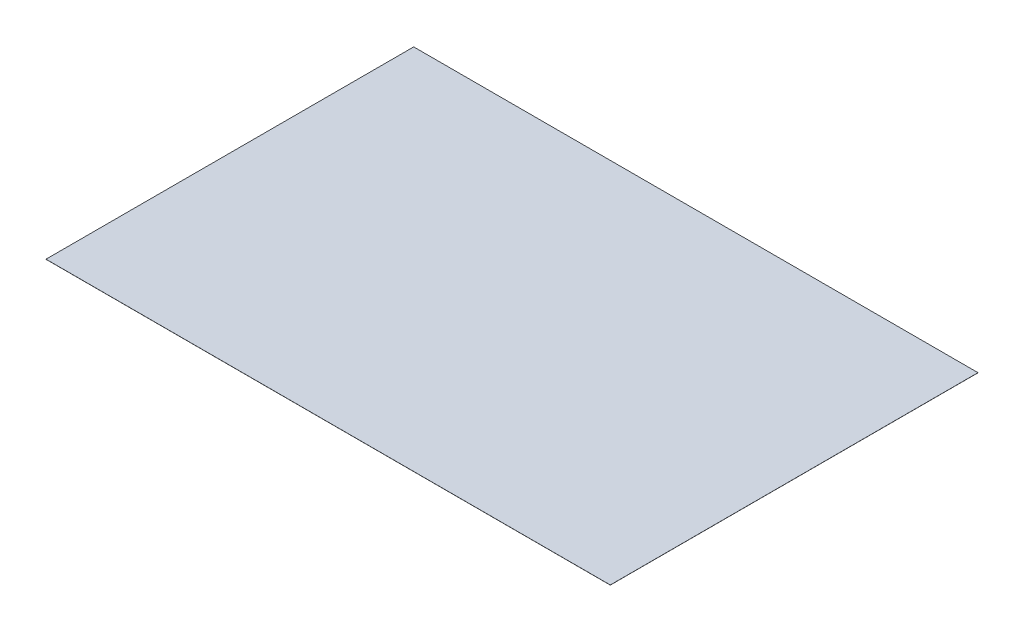
SolidWorks part; units mm, degrees
ref_plane "Front Plane" through (0, 0, 0) normal (0, 0, 1) x (1, 0, 0)
ref_plane "Top Plane" through (0, 0, 0) normal (0, 1, 0) x (1, 0, 0)
ref_plane "Right Plane" through (0, 0, 0) normal (1, 0, 0) x (0, 0, -1)
sketch "Sketch2" plane through (0, 0, 0) normal (0, 1, 0) x (1, 0, 0)
  line L1 (0, 0) -> (227.86, 0)
  line L2 (0, 0) -> (0, 148.48)
  line L3 (0, 148.48) -> (227.86, 148.48)
  line L4 (227.86, 0) -> (227.86, 148.48)
  dimension "D1" = 227.86
  dimension "D2" = 148.48
extrude "Boss-Extrude1" add sketch "Sketch2" along normal blind 0.05
